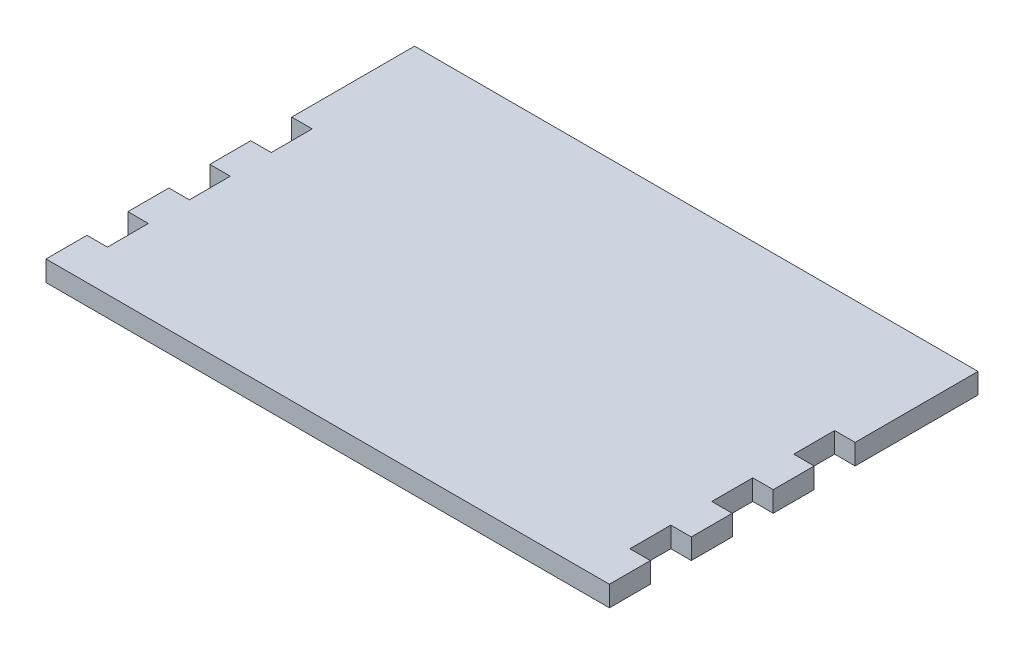
SolidWorks part; units mm, degrees
material "Acrylic (Medium-high impact)"
ref_plane "Front Plane" through (0, 0, 0) normal (0, 0, 1) x (1, 0, 0)
ref_plane "Top Plane" through (0, 0, 0) normal (0, 1, 0) x (1, 0, 0)
ref_plane "Right Plane" through (0, 0, 0) normal (1, 0, 0) x (0, 0, -1)
sketch "Sketch1" plane through (0, 0, 0) normal (0, 1, 0) x (1, 0, 0)
  line L0 (0, 0) -> (81, 0)
  line L1 (81, 6.35) -> (81, 12.7)
  line L2 (84.175, 44.45) -> (81, 44.45) construction
  line L3 (84.175, 38.1) -> (84.175, 44.45)
  line L4 (0, 0) -> (-3.175, 0)
  line L5 (-3.175, 0) -> (-3.175, 6.35)
  line L6 (-3.175, 6.35) -> (0, 6.35)
  line L7 (81, 38.1) -> (84.175, 38.1)
  line L8 (84.175, 31.75) -> (81, 31.75)
  line L9 (84.175, 25.4) -> (84.175, 31.75)
  line L10 (81, 25.4) -> (84.175, 25.4)
  line L11 (84.175, 19.05) -> (81, 19.05)
  line L12 (84.175, 12.7) -> (84.175, 19.05)
  line L13 (81, 12.7) -> (84.175, 12.7)
  line L14 (81, 31.75) -> (81, 38.1)
  line L15 (81, 19.05) -> (81, 25.4)
  line L16 (0, 44.45) -> (81, 44.45) construction
  line L17 (-3.175, 44.45) -> (-3.175, 57.15)
  line L18 (-3.175, 57.15) -> (84.175, 57.15)
  line L19 (84.175, 57.15) -> (84.175, 44.45)
  line L25 (0, 6.35) -> (0, 12.7)
  line L26 (0, 19.05) -> (0, 25.4)
  line L27 (0, 31.75) -> (0, 38.1)
  line L32 (40.5, 44.45) -> (40.5, 0) construction
  line L51 (84.175, 6.35) -> (81, 6.35)
  line L52 (84.175, 0) -> (84.175, 6.35)
  line L53 (81, 0) -> (84.175, 0)
  line L61 (0, 12.7) -> (-3.175, 12.7)
  line L62 (-3.175, 12.7) -> (-3.175, 19.05)
  line L63 (-3.175, 19.05) -> (0, 19.05)
  line L64 (0, 25.4) -> (-3.175, 25.4)
  line L65 (-3.175, 25.4) -> (-3.175, 31.75)
  line L66 (-3.175, 31.75) -> (0, 31.75)
  line L67 (0, 38.1) -> (-3.175, 38.1)
  line L68 (-3.175, 38.1) -> (-3.175, 44.45)
  line L69 (-3.175, 44.45) -> (0, 44.45) construction
  line L70 (0, 50.8) -> (-3.175, 50.8) [skipped]
  line L71 (-3.175, 50.8) -> (-3.175, 57.15) [skipped]
  line L72 (-3.175, 57.15) -> (0, 57.15) [skipped]
  line L73 (0, 63.5) -> (-3.175, 63.5) [skipped]
  line L74 (-3.175, 63.5) -> (-3.175, 69.85) [skipped]
  line L75 (-3.175, 69.85) -> (0, 69.85) [skipped]
  line L76 (0, 76.2) -> (-3.175, 76.2) [skipped]
  line L77 (-3.175, 76.2) -> (-3.175, 82.55) [skipped]
  line L78 (-3.175, 82.55) -> (0, 82.55) [skipped]
  dimension "D1" = 81
  dimension "D2" = 3.175
  dimension "D3" = 6.35
  dimension "D4" = 12.7
  dimension "D6" = 4
extrude "Boss-Extrude1" add sketch "Sketch1" along normal blind 3.175
